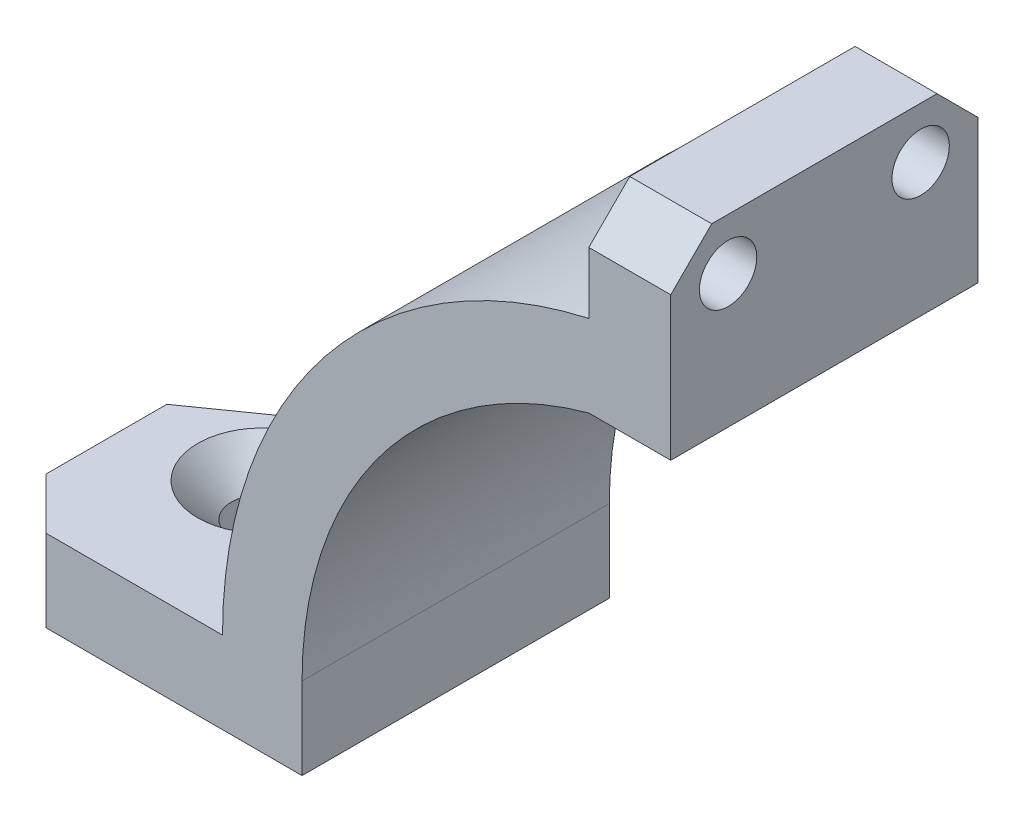
SolidWorks part; units mm, degrees
ref_plane "Front Plane" through (0, 0, 0) normal (0, 0, 1) x (1, 0, 0)
ref_plane "Top Plane" through (0, 0, 0) normal (0, 1, 0) x (1, 0, 0)
ref_plane "Right Plane" through (0, 0, 0) normal (1, 0, 0) x (0, 0, -1)
sketch "Sketch1" plane through (0, 0, 0) normal (0, 0, 1) x (1, 0, 0)
  line L0 (0, 0) -> (0, 50000) construction
  line L2 (-19, 0) -> (-19, -4)
  line L3 (-19, -4) -> (-34, -4)
  line L4 (-34, -4) -> (-34, 0)
  line L5 (-34, 0) -> (-22.8832, 0)
  line L6 (-5, 22.3303) -> (-5, 27.3303)
  line L7 (-5, 27.3303) -> (-1, 27.3303)
  line L8 (-1, 27.3303) -> (-1, 18.3303)
  line L9 (-1, 18.3303) -> (-5, 18.3303)
  arc A0 (-19, 0) -> (-5, 18.3303) centre (0, 0) cw
  arc A1 (-22.8832, 0) -> (-5, 22.3303) centre (0, 0) cw
  dimension "D2" = 19
  dimension "D1" = 4
  dimension "D3" = 15
  dimension "D4" = 4
  dimension "D5" = 4
  dimension "D6" = 9
  dimension "D7" = 1
extrude "Boss-Extrude1" add sketch "Sketch1" along normal blind 15
chamfer "Chamfer1" distance 2.5 2 edges at (-34, -2, 0) (-34, -2, 15)
sketch "Sketch2" plane through (-5, 0, 0) normal (-1, 0, 0) x (0, 0, 1)
  line L0 (15, 27.3303) -> (15, 22.3303) construction
  line L1 (0, 27.3303) -> (0, 22.3303) construction
  circle A0 centre (2.8, 24.8303) radius 1.4
  circle A1 centre (12.2, 24.8303) radius 1.4
  point P8 (0, 24.8303)
  dimension "D1" = 2.8
  dimension "D2" = 2.8
  dimension "D3" = 2.8
extrude "Cut-Extrude1" cut sketch "Sketch2" against normal blind 15
chamfer "Chamfer2" distance 2 angle 45 2 edges at (-3, 27.3303, 15) (-3, 27.3303, 0)
sketch "Sketch3" plane through (0, 0, 0) normal (0, 1, 0) x (1, 0, 0)
  line L0 (-34, -12.5) -> (-34, -2.5) construction
  line L2 (-22.8832, 0) -> (-34, 0.1) construction
  line L3 (45.4373, 0.1) -> (-44.4791, 0.1) construction
  circle A0 centre (-28.4416, -7.5) radius 1.4
  point P2 (-28.4416, 0.05)
  point P5 (-34, -7.5)
  dimension "D1" = 2.8
extrude "Cut-Extrude2" cut sketch "Sketch3" against normal through all contours A0
sketch "Sketch4" plane through (0, -4, 0) normal (0, -1, 0) x (1, 0, 0)
  line L0 (-24.6361, 0) -> (-34, 6.6004)
  line L1 (-31.5, 0) -> (-19, 0) construction
  line L2 (-34, 12.5) -> (-34, 2.5) construction
  line L3 (-34, 6.6004) -> (-34, 2.5)
  line L4 (-34, 2.5) -> (-31.5, 0)
  line L5 (-34, 2.5) -> (-31.5, 0) construction
  line L6 (-31.5, 0) -> (-24.6361, 0)
extrude "Cut-Extrude3" cut sketch "Sketch4" against normal blind 25 contours L6 L0 L3 L4
hole_wizard "CSK for M3 Flat Head Machine Screw1" positions "Sketch5" profile "Sketch6" countersink size "M3" standard "ANSI Metric"
sketch "Sketch5" plane through (0, 0, 0) normal (0, 1, 0) x (1, 0, 0)
  point P0 (-28.4416, -7.5)
sketch "Sketch6" plane through (-28.4416, 0, 7.5) normal (1, 0, 0) x (0, 0, 1)
  line L0 (0, 0) -> (0, 32)
  line L1 (0, 32) -> (1.5, 31.0987)
  line L2 (1.5, 31.0987) -> (1.5, 1.65)
  line L3 (1.5, 1.65) -> (3.15, 0)
  line L5 (3.15, 0) -> (0, 0)
  line L6 (-1.5, 1.65) -> (-3.15, 0) construction
  line L10 (0, 32) -> (-1.5, 31.0987) construction
  line L11 (0, -6.35) -> (0, 107.95) construction
  dimension "Hole Dia." = 3
  dimension "Hole Depth" = 32
  dimension "Near C'Sink Dia." = 6.3
  dimension "Near C'Sink Angle" = 90
  dimension "Drill Angle" = 118
